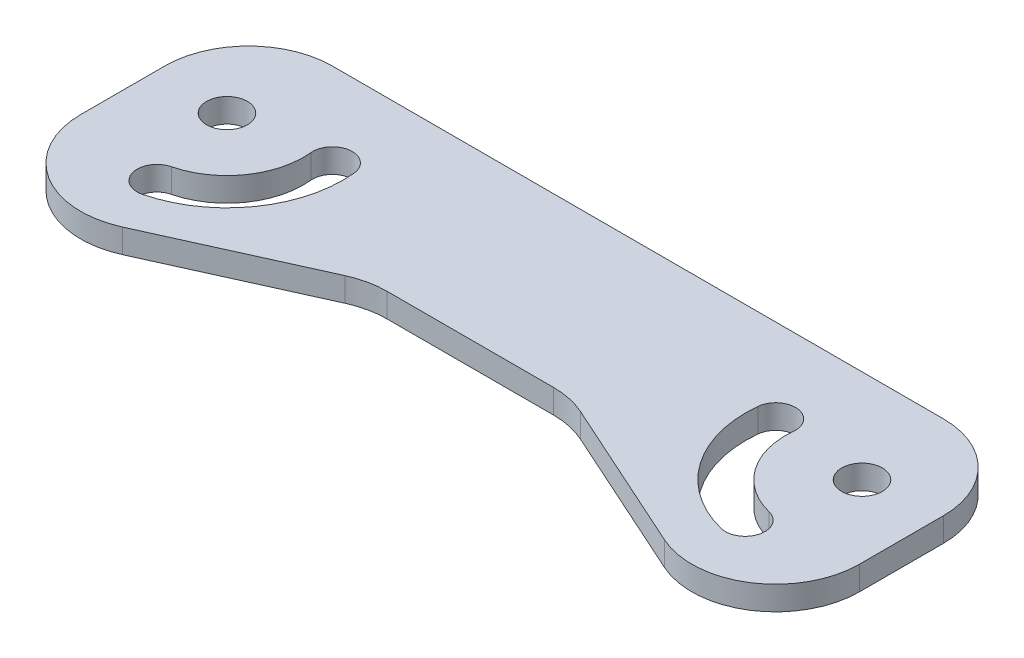
SolidWorks part; units mm, degrees
ref_plane "Front Plane" through (0, 0, 0) normal (0, 0, 1) x (1, 0, 0)
ref_plane "Top Plane" through (0, 0, 0) normal (0, 1, 0) x (1, 0, 0)
ref_plane "Right Plane" through (0, 0, 0) normal (1, 0, 0) x (0, 0, -1)
sketch "Sketch1" plane through (0, 0, 0) normal (0, 1, 0) x (1, 0, 0)
  line L1 (-32.5, 7) -> (32.5, 7)
  line L2 (-32.5, 7) -> (-32.5, -7)
  line L3 (-32.5, -7) -> (32.5, -7)
  line L4 (32.5, 7) -> (32.5, -7)
  line L5 (-32.5, 7) -> (32.5, -7) construction
  line L6 (-32.5, -7) -> (32.5, 7) construction
  point P0 (0, 0)
  dimension "D1" = 65
  dimension "D2" = 14
extrude "Boss-Extrude1" add sketch "Sketch1" along normal blind 2
sketch "Sketch5" plane through (0, 2, 0) normal (0, 1, 0) x (1, 0, 0)
  line L0 (-32.5, -7) -> (-32.5, -17.85)
  line L1 (-32.5, -17.85) -> (-8.45, -7)
  line L2 (-32.5, -7) -> (32.5, -7) construction
  line L3 (-8.45, -7) -> (-32.5, -7)
  line L4 (0, 0) -> (0, -21.0415) construction
  line L5 (8.45, -7) -> (32.5, -7)
  line L6 (32.5, -17.85) -> (8.45, -7)
  line L7 (32.5, -7) -> (32.5, -17.85)
  dimension "D1" = 10.85
  dimension "D2" = 16.9
extrude "Boss-Extrude2" add sketch "Sketch5" against normal up to surface (2 mm away) up to face at (0, 0, 0)
hole_wizard "M3 Clearance Hole1" positions "Sketch3" profile "Sketch2" hole size "M3" standard "ANSI Metric" end condition through all
sketch "Sketch3" plane through (0, 2, 0) normal (0, 1, 0) x (1, 0, 0)
  line L0 (0, 0) -> (0, 18.1503) construction
  point P0 (-26.5, -0.8)
  point P9 (26.5, -0.8)
  dimension "D1" = 26.5
  dimension "D2" = 17.05
sketch "Sketch2" plane through (-26.5, 2, 0.8) normal (1, 0, 0) x (0, 0, 1)
  line L0 (0, 0) -> (0, 2.0001)
  line L1 (0, 2.0001) -> (1.7, 2.0001)
  line L2 (1.7, 2.0001) -> (1.7, 0)
  line L5 (1.7, 0) -> (0, 0)
  line L11 (0, -6.35) -> (0, 107.95) construction
  dimension "Thru Hole Dia." = 3.4
  dimension "Thru Hole Depth" = 2.0001
sketch "Sketch4" plane through (0, 2, 0) normal (0, 1, 0) x (1, 0, 0)
  line L0 (0, 0) -> (0, 21.5922) construction
  arc A0 (-24.55, -8.5998) -> (-18.5, 0) centre (-26.5, -0.8) ccw construction
  arc A1 (-24.1498, -10.2006) -> (-16.8582, 0.1642) centre (-26.5, -0.8) ccw
  arc A2 (-24.9502, -6.9991) -> (-20.1418, -0.1642) centre (-26.5, -0.8) ccw
  arc A3 (-24.9502, -6.9991) -> (-24.1498, -10.2006) centre (-24.55, -8.5998) ccw
  arc A4 (-16.8582, 0.1642) -> (-20.1418, -0.1642) centre (-18.5, 0) ccw
  arc A5 (24.55, -8.5998) -> (18.5, 0) centre (26.5, -0.8) cw construction
  arc A6 (24.1498, -10.2006) -> (16.8582, 0.1642) centre (26.5, -0.8) cw
  arc A7 (24.9502, -6.9991) -> (20.1418, -0.1642) centre (26.5, -0.8) cw
  arc A8 (24.9502, -6.9991) -> (24.1498, -10.2006) centre (24.55, -8.5998) cw
  arc A9 (16.8582, 0.1642) -> (20.1418, -0.1642) centre (18.5, 0) cw
  point P4 (-19.9243, -5.426)
  point P15 (19.9243, -5.426)
  dimension "D1" = 3.3
  dimension "D2" = 1.95
  dimension "D3" = 0.8
  dimension "D4" = 8
extrude "Cut-Extrude1" cut sketch "Sketch4" against normal through all
fillet "Fillet1" radius 7 6 edges at (32.5, 1, -7) (-32.5, 1, -7) (32.5, 1, 17.85) (8.45, 1, 7) (-32.5, 1, 17.85)
